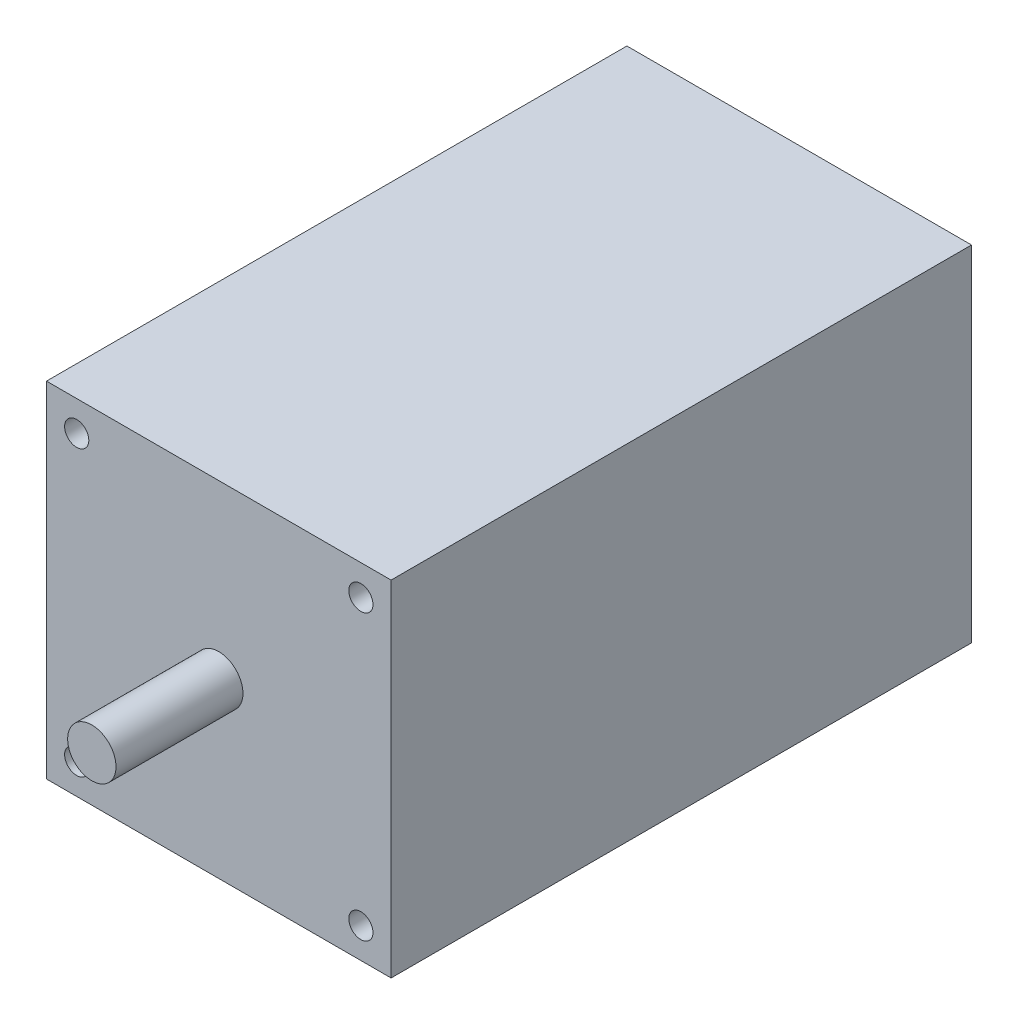
SolidWorks part; units mm, degrees
ref_plane "前基準面" through (0, 0, 0) normal (0, 0, 1) x (1, 0, 0)
ref_plane "上基準面" through (0, 0, 0) normal (0, 1, 0) x (1, 0, 0)
ref_plane "右基準面" through (0, 0, 0) normal (1, 0, 0) x (0, 0, -1)
sketch "草圖1" plane through (0, 0, 0) normal (0, 0, 1) x (1, 0, 0)
  line L1 (28.5, 28.5) -> (-28.5, 28.5)
  line L2 (28.5, 28.5) -> (28.5, -28.5)
  line L3 (28.5, -28.5) -> (-28.5, -28.5)
  line L4 (-28.5, 28.5) -> (-28.5, -28.5)
  line L5 (0, -28.5) -> (0, 28.5) construction
  line L6 (28.5, 0) -> (-28.5, 0) construction
  circle A0 centre (0, 0) radius 4 construction
  circle A1 centre (-23.5, 23.5) radius 2
  circle A2 centre (23.5, 23.5) radius 2
  circle A3 centre (23.5, -23.5) radius 2
  circle A4 centre (-23.5, -23.5) radius 2
  point P0 (0, 0)
  dimension "D3" = 8
  dimension "D4" = 4
  dimension "D1" = 57
  dimension "D2" = 57
  dimension "D5" = 47
  dimension "D6" = 47
extrude "填料-伸長1" add sketch "草圖1" against normal blind 96
sketch "草圖2" plane through (0, 0, 0) normal (0, 0, 1) x (1, 0, 0)
  circle A0 centre (0, 0) radius 4
  dimension "D1" = 8
extrude "填料-伸長2" add sketch "草圖2" along normal blind 21
